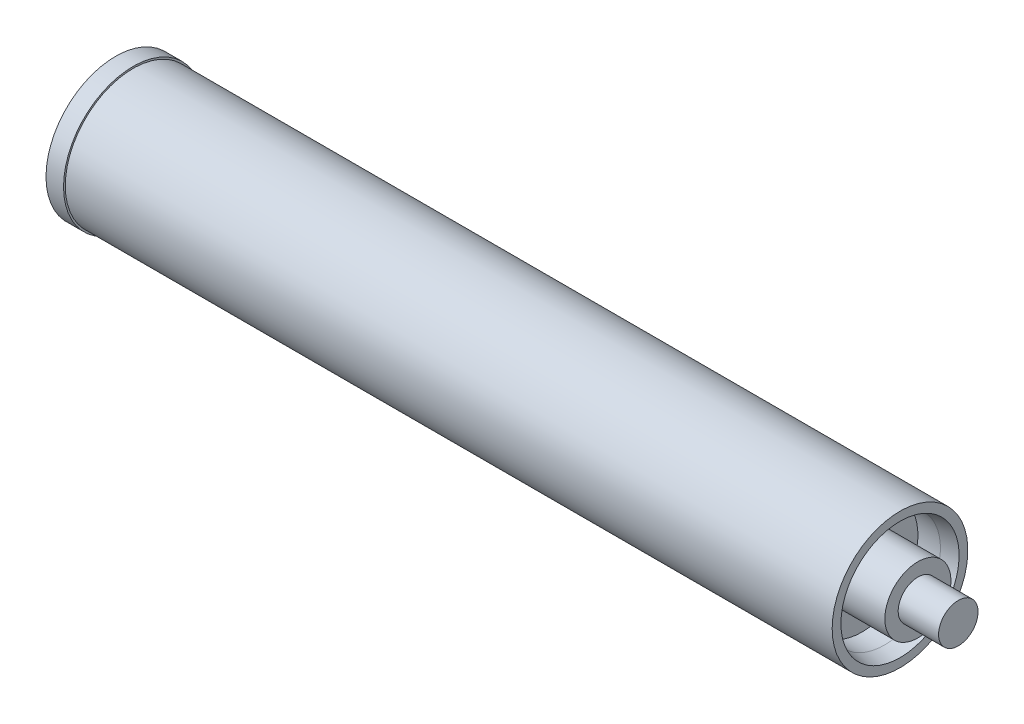
SolidWorks part; units mm, degrees
ref_plane "Plan de face" through (0, 0, 0) normal (0, 0, 1) x (1, 0, 0)
ref_plane "Plan de dessus" through (0, 0, 0) normal (0, 1, 0) x (1, 0, 0)
ref_plane "Plan de droite" through (0, 0, 0) normal (1, 0, 0) x (0, 0, -1)
sketch "Esquisse2" plane through (0, 0, 0) normal (0, 0, 1) x (1, 0, 0)
  line L0 (0, 0) -> (97.8436, 0) construction
  line L1 (0, -26) -> (0, 26) construction
  line L2 (0, 26) -> (12.7, 26)
  line L3 (12.7, 26) -> (12.7, 50.419) construction
  line L4 (12.7, 50.419) -> (25.4, 50.419)
  line L5 (25.4, 50.419) -> (25.4, 49.149)
  line L6 (25.4, 49.149) -> (581.02, 49.149)
  line L7 (581.02, 49.149) -> (581.02, 42.8202)
  line L8 (581.02, 42.8202) -> (569.6971, 40.5731)
  line L9 (569.6971, 40.5731) -> (553.412, 40.5731)
  line L10 (553.412, 40.5731) -> (553.412, 23.9395)
  line L11 (553.412, 23.9395) -> (593.98, 23.9395)
  line L12 (593.98, 23.9395) -> (593.98, 14.2875)
  line L13 (593.98, 14.2875) -> (623.27, 14.2875)
  line L14 (623.27, 14.2875) -> (623.27, -14.2875) construction
  line L15 (623.27, 0) -> (0, 0) construction
  line L16 (593.98, -14.2875) -> (623.27, -14.2875) construction
  line L17 (593.98, -23.9395) -> (593.98, -14.2875) construction
  line L18 (553.412, -23.9395) -> (593.98, -23.9395) construction
  line L19 (553.412, -40.5731) -> (553.412, -23.9395) construction
  line L20 (569.6971, -40.5731) -> (553.412, -40.5731) construction
  line L21 (581.02, -42.8202) -> (569.6971, -40.5731) construction
  line L22 (581.02, -49.149) -> (581.02, -42.8202) construction
  line L23 (25.4, -49.149) -> (581.02, -49.149) construction
  line L24 (25.4, -50.419) -> (25.4, -49.149) construction
  line L25 (12.7, -50.419) -> (25.4, -50.419) construction
  line L26 (12.7, -26) -> (12.7, -50.419) construction
  line L27 (0, -26) -> (12.7, -26) construction
  line L28 (12.7, 50.419) -> (12.7, 38.2095)
  line L29 (12.7, 38.2095) -> (25.4, 35.6891)
  line L30 (25.4, 35.6891) -> (36.5674, 35.6891)
  line L31 (36.5674, 35.6891) -> (36.5674, 26)
  line L32 (36.5674, 26) -> (12.7, 26)
  line L33 (25.4, 35.6891) -> (25.4, 49.149) construction
  line L34 (36.5674, -26) -> (12.7, -26) construction
  line L35 (36.5674, -35.6891) -> (36.5674, -26) construction
  line L36 (25.4, -35.6891) -> (36.5674, -35.6891) construction
  line L37 (12.7, -38.2095) -> (25.4, -35.6891) construction
  line L38 (12.7, -50.419) -> (12.7, -38.2095) construction
  line L39 (0, 26) -> (0, 0)
  line L40 (0, 0) -> (623.27, 0)
  line L41 (623.27, 0) -> (623.27, 14.2875)
  dimension "D2" = 555.62
  dimension "D3" = 568.58
  dimension "D4" = 28.575
  dimension "D5" = 47.879
  dimension "D6" = 98.298
  dimension "D7" = 12.7
  dimension "D8" = 100.838
  dimension "D9" = 12.7
  dimension "D10" = 52
  dimension "D11" = 597.87
revolve "Révolution7" add sketch "Esquisse2" angle 360 about L0
sketch "Esquisse3" plane through (0, 0, 0) normal (0, 0, 1) x (1, 0, 0)
  line L0 (0, 0) -> (623.27, 0) construction
  line L1 (623.27, -14.2875) -> (623.27, 14.2875) construction
  line L2 (0, 20) -> (0, 0)
  line L3 (0, 26) -> (0, -26) construction
  line L4 (0, 0) -> (390.0908, 0)
  line L5 (390.0908, 0) -> (553.412, 12.9578)
  line L6 (553.412, -40.5731) -> (553.412, 40.5731) construction
  line L7 (553.412, 12.9578) -> (381.0611, 12.9578)
  line L8 (381.0611, 12.9578) -> (381.0611, 44.271)
  line L9 (381.0611, 44.271) -> (65.8719, 44.271)
  line L10 (65.8719, 44.271) -> (34.083, 14.3276)
  line L11 (34.083, 14.3276) -> (19.083, 14.3276)
  line L12 (19.083, 14.3276) -> (0, 20)
  line L13 (36.5674, 26) -> (0, 26) construction
  dimension "D1" = 15
  dimension "D2" = 6
revolve "Enlèvement de matière-Révolution1" cut sketch "Esquisse3" angle 360 about L0
